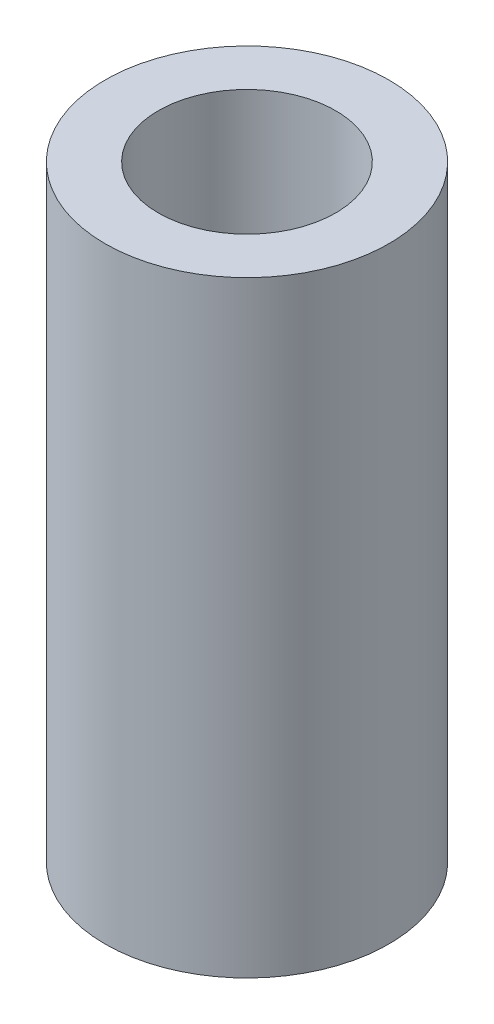
SolidWorks part; units mm, degrees
ref_plane "Front Plane" through (0, 0, 0) normal (0, 0, 1) x (1, 0, 0)
ref_plane "Top Plane" through (0, 0, 0) normal (0, 1, 0) x (1, 0, 0)
ref_plane "Right Plane" through (0, 0, 0) normal (1, 0, 0) x (0, 0, -1)
sketch "Sketch1" plane through (0, 0, 0) normal (0, 1, 0) x (1, 0, 0)
  circle A0 centre (0, 0) radius 1.25
  circle A1 centre (0, 0) radius 2
  dimension "D1" = 2.5
  dimension "D2" = 4
extrude "Boss-Extrude1" add sketch "Sketch1" along normal blind 8.55
